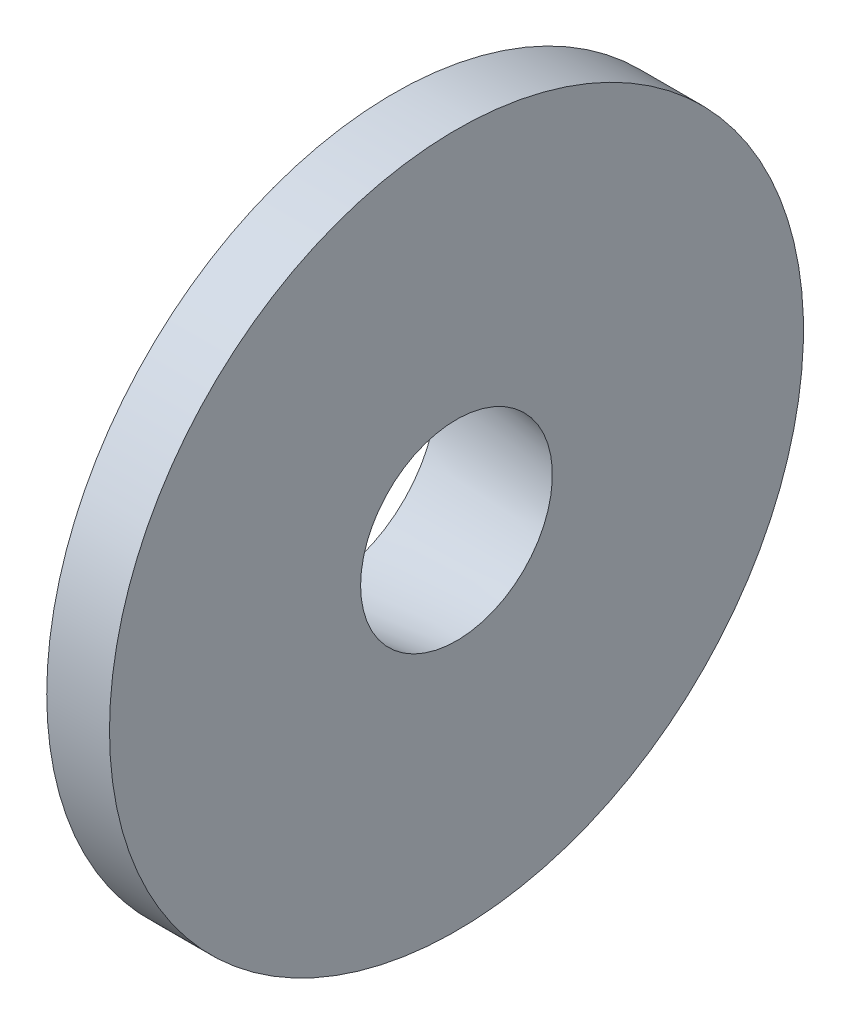
SolidWorks part; units mm, degrees
ref_plane "Plan de face" through (0, 0, 0) normal (0, 0, 1) x (1, 0, 0)
ref_plane "Plan de dessus" through (0, 0, 0) normal (0, 1, 0) x (1, 0, 0)
ref_plane "Plan de droite" through (0, 0, 0) normal (1, 0, 0) x (0, 0, -1)
sketch "Esquisse1" plane through (191.924, -30.4842, 0) normal (0, 0, 1) x (1, 0, 0)
  line L0 (-191.924, 48.3842) -> (-191.924, 62.3842)
  line L1 (-191.924, 62.3842) -> (-180.924, 85.7592)
  line L2 (-180.924, 85.7592) -> (-170.924, 85.7592)
  line L3 (-170.924, 85.7592) -> (-170.924, 45.7592)
  line L4 (-170.924, 45.7592) -> (-191.924, 48.3842)
  line L5 (-53.3284, 30.4842) -> (89.8724, 30.4842) construction
  point P9 (-191.924, 30.4842)
  dimension "D1" = 14
  dimension "D2" = 21
  dimension "D3" = 10
  dimension "D4" = 40
  dimension "D5" = 17.9
  dimension "D6" = 82.875
revolve "Révolution1" add sketch "Esquisse1" angle 360 about L5
